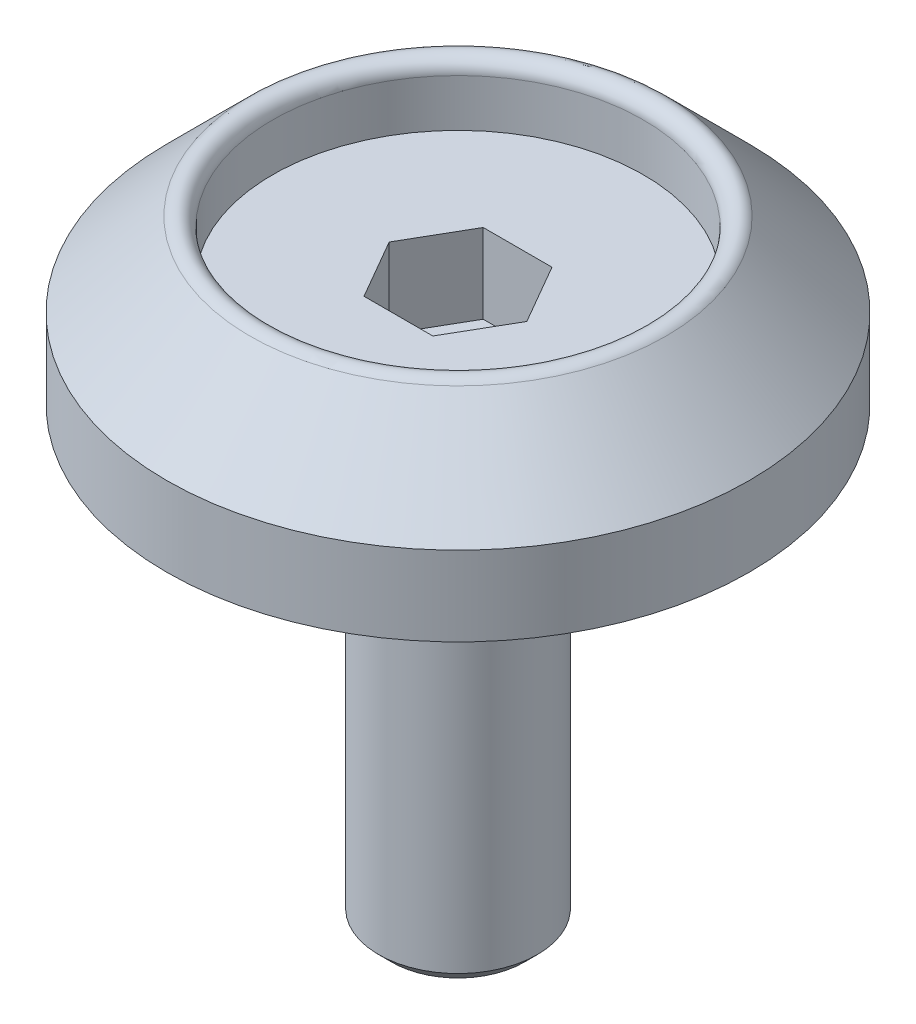
SolidWorks part; units mm, degrees
ref_plane "Face" through (0, 0, 0) normal (0, 0, 1) x (1, 0, 0)
ref_plane "Dessus" through (0, 0, 0) normal (0, 1, 0) x (1, 0, 0)
ref_plane "Droite" through (0, 0, 0) normal (1, 0, 0) x (0, 0, -1)
sketch "Esquisse1" plane through (0, 0, 0) normal (0, 0, 1) x (1, 0, 0)
  line L0 (0, 0) -> (1.25, 0)
  line L1 (1.5, 0.25) -> (1.5, 8.5)
  line L2 (1.5, 8.5) -> (5.5, 8.5)
  line L3 (5.5, 8.5) -> (5.5, 10)
  line L4 (5.5, 10) -> (3.9268, 11.5732)
  line L5 (0, 10.5) -> (3.5, 10.5)
  line L6 (0, 10.5) -> (0, 0)
  line L7 (3.5, 10.5) -> (3.5, 11.3964)
  line L8 (0, -3.1203) -> (0, 14.2384) construction
  line L9 (1.25, 0) -> (1.5, 0.25)
  arc A0 (3.9268, 11.5732) -> (3.5, 11.3964) centre (3.75, 11.3964) ccw
  point P1 (1.5, 0)
  point P10 (3.5, 12)
  dimension "D8" = 0.25
  dimension "D1" = 3.5
  dimension "D2" = 5.5
  dimension "D3" = 1.5
  dimension "D4" = 8.5
  dimension "D5" = 1.5
  dimension "D6" = 45
  dimension "D7" = 1.5
  dimension "D11" = 0.25
revolve "Base-Révolution" add sketch "Esquisse1" angle 360 about L8
sketch "Esquisse2" plane through (0, 10.5, 0) normal (0, 1, 0) x (-1, 0, 0)
  line L0 (-0.6495, 1.125) -> (0.6495, 1.125)
  line L1 (0.6495, 1.125) -> (1.299, 0)
  line L2 (1.299, 0) -> (0.6495, -1.125)
  line L3 (0.6495, -1.125) -> (-0.6495, -1.125)
  line L4 (-0.6495, -1.125) -> (-1.299, 0)
  line L5 (-1.299, 0) -> (-0.6495, 1.125)
  circle A0 centre (0, 0) radius 1.125 construction
  dimension "D1" = 2.25
  dimension "D2" = 120
  dimension "D3" = 120
  dimension "D4" = 120
  dimension "D5" = 120
  dimension "D6" = 120
extrude "Enlèv. mat.-Extru.1" cut sketch "Esquisse2" against normal blind 1.5
